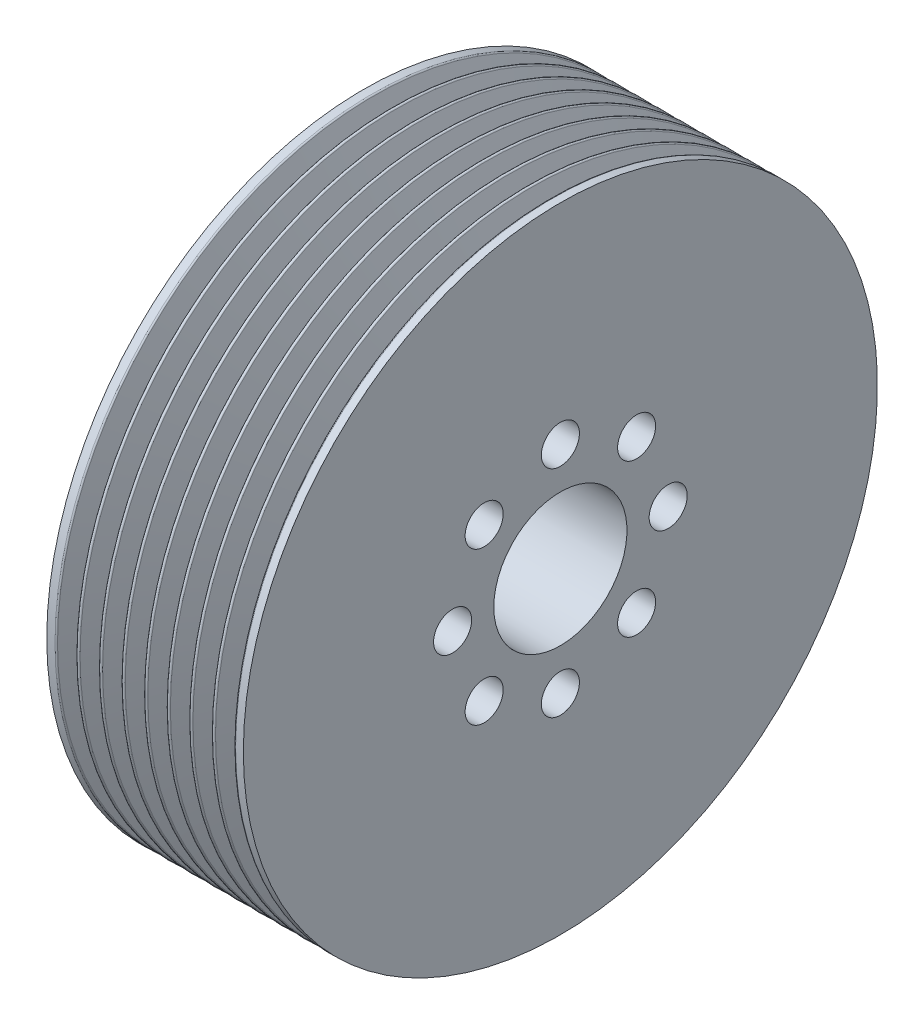
SolidWorks part; units mm, degrees
material "2018 Alloy"
ref_plane "Front Plane" through (0, 0, 0) normal (0, 0, 1) x (1, 0, 0)
ref_plane "Top Plane" through (0, 0, 0) normal (0, 1, 0) x (1, 0, 0)
ref_plane "Right Plane" through (0, 0, 0) normal (1, 0, 0) x (0, 0, -1)
sketch "Sketch1" plane through (0, 0, 0) normal (0, 0, 1) x (1, 0, 0)
  line L0 (49, 10.5) -> (49, 0) construction
  line L1 (49, 10.5) -> (49, 50)
  line L2 (49, 50) -> (18, 50)
  line L3 (18, 50) -> (18, 21.5)
  line L4 (49, 10.5) -> (31.5, 10.5)
  line L5 (0, 0) -> (49, 0) construction
  line L6 (18, 21.5) -> (31.5, 21.5)
  line L8 (0, 8.3175) -> (0, 0) construction
  line L9 (31.5, 10.5) -> (31.5, 21.5)
  dimension "D1" = 31
  dimension "D2" = 100
  dimension "D3" = 31.5
  dimension "D4" = 43
  dimension "D5" = 49
  dimension "D8" = 21
revolve "Revolve1" add sketch "Sketch1" angle 360 about L5
sketch "Sketch2" plane through (0, 0, 0) normal (0, 0, 1) x (1, 0, 0)
  line L0 (47.5458, 49.8376) -> (46.281, 46.4546)
  line L1 (45.719, 46.4546) -> (44.4542, 49.8376)
  line L2 (47.5458, 49.8376) -> (47.6066, 50) construction
  line L3 (49, 50) -> (18, 50) construction
  line L4 (44.4542, 49.8376) -> (44.3934, 50) construction
  line L5 (49, -50) -> (49, 50) construction
  line L6 (47.78, 50) -> (44.22, 50)
  line L7 (0, 0) -> (49, 0) construction
  arc A0 (47.5458, 49.8376) -> (47.78, 50) centre (47.78, 49.75) cw
  arc A1 (44.4542, 49.8376) -> (44.22, 50) centre (44.22, 49.75) ccw
  arc A2 (46.281, 46.4546) -> (45.719, 46.4546) centre (46, 46.5597) cw
  dimension "D2" = 0.25
  dimension "D3" = 0.3
  dimension "D1" = 41
  dimension "D4" = 3.56
  dimension "D5" = 3
revolve "Cut-Revolve1" cut sketch "Sketch2" angle 360 about L7
pattern_linear "LPattern1" count 8 spacing 3.56 along (-1, 0, 0) of "Cut-Revolve1"
sketch "Sketch3" plane through (49, 0, 0) normal (1, 0, 0) x (0, 0, -1)
  circle A0 centre (0, 0) radius 17 construction
  circle A1 centre (0, 17) radius 3
  circle A2 centre (12.0208, 12.0208) radius 3
  circle A3 centre (17, 0) radius 3
  circle A4 centre (12.0208, -12.0208) radius 3
  circle A5 centre (0, -17) radius 3
  circle A6 centre (-12.0208, -12.0208) radius 3
  circle A7 centre (-17, 0) radius 3
  circle A8 centre (-12.0208, 12.0208) radius 3
  dimension "D1" = 34
  dimension "D2" = 6
  dimension "D3" = 8
extrude "Cut-Extrude1" cut sketch "Sketch3" against normal up to surface (17.5 mm away) up to face at (31.5, 0, 10.5)
